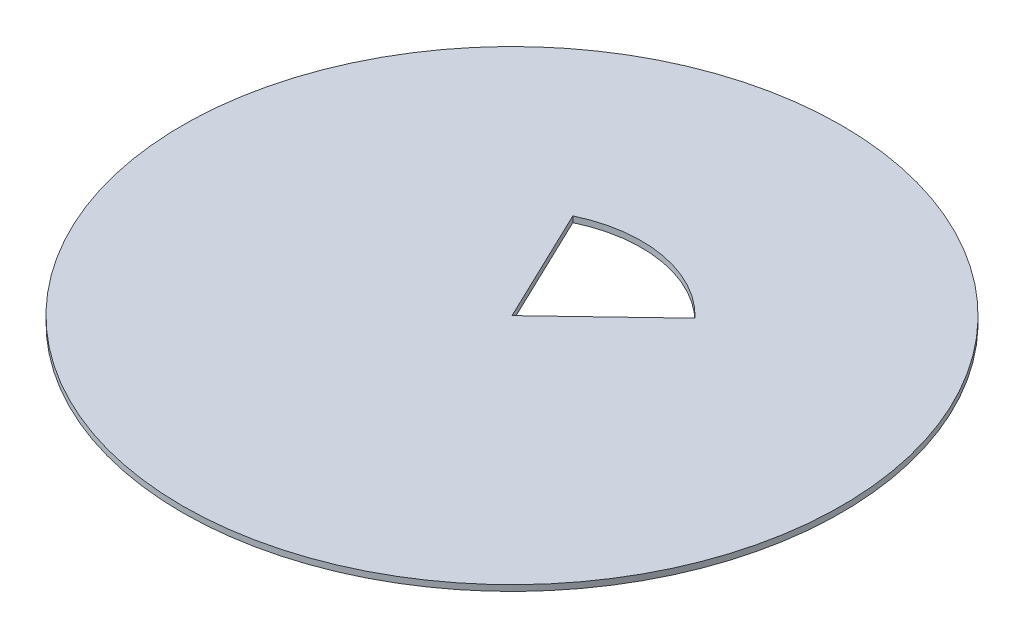
SolidWorks part; units mm, degrees
material "Acrylic (Medium-high impact)"
ref_plane "Front" through (0, 0, 0) normal (0, 0, 1) x (1, 0, 0)
ref_plane "Top" through (0, 0, 0) normal (0, 1, 0) x (1, 0, 0)
ref_plane "Right" through (0, 0, 0) normal (1, 0, 0) x (0, 0, -1)
sketch "Sketch1" plane through (0, 0, 0) normal (0, 1, 0) x (1, 0, 0)
  circle A0 centre (0, 0) radius 177.8
  dimension "D1" = 355.6
extrude "Boss-Extrude1" add sketch "Sketch1" along normal blind 3.175
sketch "Sketch2" plane through (0, 3.175, 0) normal (0, 1, 0) x (1, 0, 0)
  line L0 (-76.8005, 160.3575) -> (0, 0) construction
  line L1 (0, 0) -> (128.7764, 122.5948) construction
  line L2 (0, 0) -> (-176.2417, -23.4884) construction
  line L3 (0, 0) -> (-32.1229, -174.8741) construction
  line L4 (0, 0) -> (156.3887, -84.5897) construction
  line L5 (78.1943, -42.2949) -> (64.3882, 61.2974) construction
  line L6 (64.3882, 61.2974) -> (-38.4002, 80.1787) construction
  line L7 (-38.4002, 80.1787) -> (-88.1208, -11.7442) construction
  line L8 (-88.1208, -11.7442) -> (-16.0614, -87.4371) construction
  line L9 (-16.0614, -87.4371) -> (78.1943, -42.2949) construction
  circle A0 centre (0, 0) radius 177.8 construction
sketch "Sketch3" plane through (0, 3.175, 0) normal (0, 1, 0) x (1, 0, 0)
  line L0 (-76.8005, 160.3575) -> (0, 0) construction
  line L1 (0, 0) -> (128.7764, 122.5948) construction
  line L2 (-30.1716, 62.9976) -> (0, 0)
  line L3 (0, 0) -> (50.5907, 48.1622)
  arc A0 (-30.1716, 62.9976) -> (50.5907, 48.1622) centre (0, 0) cw
  dimension "D1" = 69.85
  dimension "D2" = 69.85
extrude "Cut-Extrude1" cut sketch "Sketch3" against normal up to next
